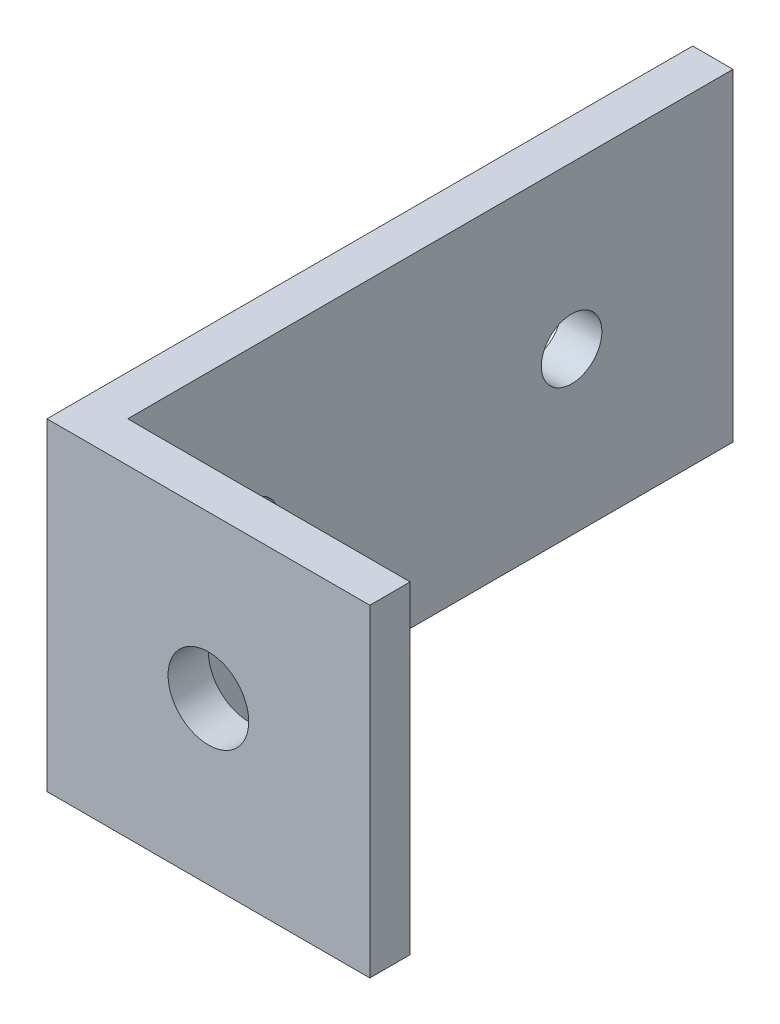
SolidWorks part; units mm, degrees
ref_plane "Front Plane" through (0, 0, 0) normal (0, 0, 1) x (1, 0, 0)
ref_plane "Top Plane" through (0, 0, 0) normal (0, 1, 0) x (1, 0, 0)
ref_plane "Right Plane" through (0, 0, 0) normal (1, 0, 0) x (0, 0, -1)
sketch "Sketch1" plane through (0, 0, 0) normal (0, 1, 0) x (1, 0, 0)
  line L1 (-3.175, 47.625) -> (0, 47.625)
  line L2 (-3.175, 47.625) -> (-3.175, -3.175)
  line L3 (-3.175, -3.175) -> (4.2596, -3.175)
  line L4 (0, 47.625) -> (0, 0)
  line L7 (0, 0) -> (22.225, 0)
  line L9 (4.2596, -3.175) -> (22.225, -3.175)
  line L10 (22.225, 0) -> (22.225, -3.175)
  point P0 (0, 13.9621)
  dimension "D1" = 50.8
  dimension "D2" = 25.4
  dimension "D3" = 3.175
  dimension "D4" = 3.175
extrude "Boss-Extrude1" add sketch "Sketch1" along normal blind 25.4
sketch "Sketch2" plane through (0, 0, 0) normal (0, 0, -1) x (-1, 0, 0)
  line L0 (0, 12.7) -> (-22.225, 12.7) construction
  line L1 (0, 25.4) -> (0, 0) construction
  line L2 (-22.225, 25.4) -> (-22.225, 0) construction
  circle A0 centre (-9.525, 12.7) radius 3.175
  dimension "D1" = 6.35
  dimension "D2" = 12.7
extrude "Cut-Extrude1" cut sketch "Sketch2" against normal through all
sketch "Sketch3" plane through (-3.175, 0, 0) normal (-1, 0, 0) x (0, 0, 1)
  line L0 (3.175, 12.7) -> (-47.625, 12.7) construction
  line L1 (3.175, 25.4) -> (3.175, 0) construction
  line L2 (-47.625, 25.4) -> (-47.625, 0) construction
  circle A0 centre (-9.525, 12.7) radius 2.3813
  circle A1 centre (-34.925, 12.7) radius 2.3812
  dimension "D1" = 4.7625
  dimension "D2" = 12.7
  dimension "D3" = 25.4
extrude "Cut-Extrude2" cut sketch "Sketch3" against normal through all
